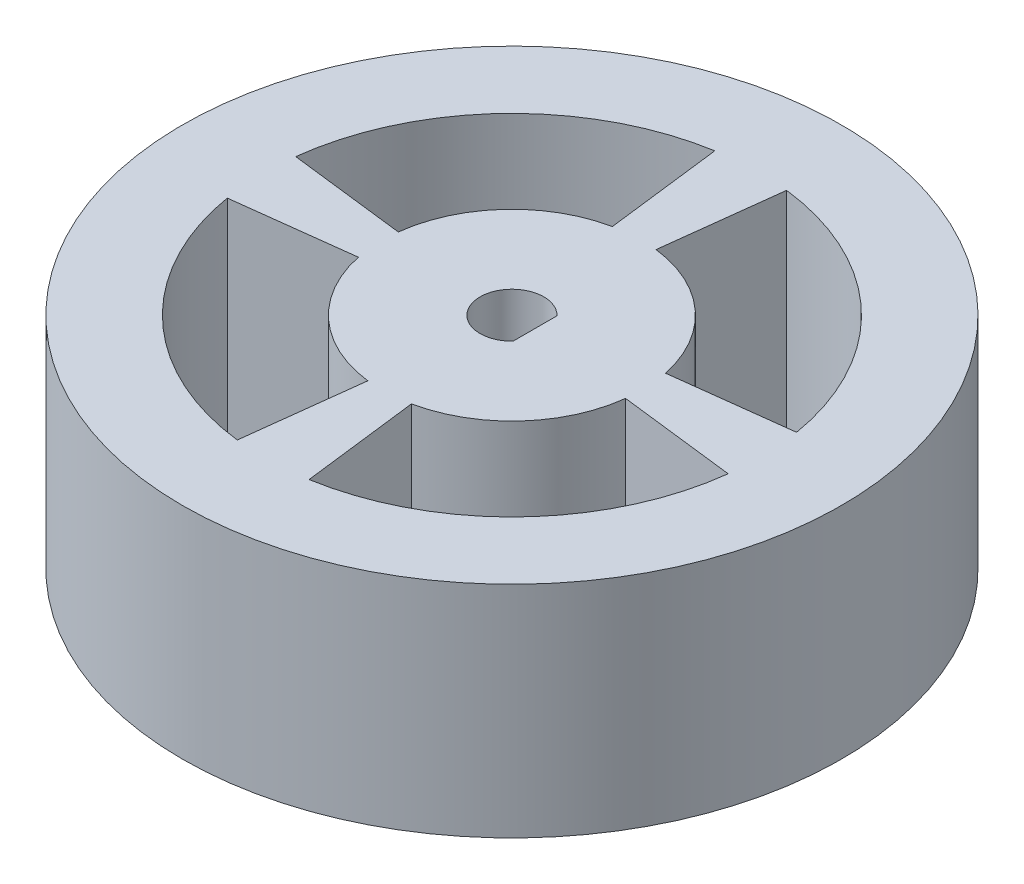
SolidWorks part; units mm, degrees
ref_plane "Plano frontal" through (0, 0, 0) normal (0, 0, 1) x (1, 0, 0)
ref_plane "Plano superior" through (0, 0, 0) normal (0, 1, 0) x (1, 0, 0)
ref_plane "Plano direito" through (0, 0, 0) normal (1, 0, 0) x (0, 0, -1)
sketch "Esboço1" plane through (0, 0, 0) normal (0, 1, 0) x (1, 0, 0)
  line L0 (-1.45, 0) -> (1.05, 0) construction
  line L1 (1.05, -1) -> (1.05, 1)
  line L2 (1.2085, -5.7812) -> (1.8617, -11.0949)
  line L3 (5.8652, -0.6936) -> (11.1711, -1.33)
  line L4 (-5.7812, -1.2085) -> (-11.0949, -1.8617)
  line L5 (-0.6936, -5.8652) -> (-1.33, -11.1711)
  line L6 (-1.2085, 5.7812) -> (-1.8617, 11.0949)
  line L7 (-5.8652, 0.6936) -> (-11.1711, 1.33)
  line L8 (5.7812, 1.2085) -> (11.0949, 1.8617)
  line L9 (0.6936, 5.8652) -> (1.33, 11.1711)
  circle A0 centre (0, 0) radius 15
  circle A1 centre (0, 0) radius 1.45 construction
  arc A3 (1.05, -1) -> (1.05, 1) centre (0, 0) cw
  circle A4 centre (0, 0) radius 5.9061 construction
  circle A5 centre (0, 0) radius 11.25 construction
  arc A6 (5.8652, -0.6936) -> (1.2085, -5.7812) centre (0, 0) cw
  arc A7 (11.1711, -1.33) -> (1.8617, -11.0949) centre (0, 0) cw
  arc A8 (-0.6936, -5.8652) -> (-5.7812, -1.2085) centre (0, 0) cw
  arc A9 (-1.33, -11.1711) -> (-11.0949, -1.8617) centre (0, 0) cw
  arc A10 (-5.8652, 0.6936) -> (-1.2085, 5.7812) centre (0, 0) cw
  arc A11 (-11.1711, 1.33) -> (-1.8617, 11.0949) centre (0, 0) cw
  arc A12 (0.6936, 5.8652) -> (5.7812, 1.2085) centre (0, 0) cw
  arc A13 (1.33, 11.1711) -> (11.0949, 1.8617) centre (0, 0) cw
  point P9 (1.05, 0)
  point P30 (0, 0)
  dimension "D1" = 30
  dimension "D2" = 2.9
  dimension "D5" = 22.5
  dimension "D3" = 2.5
  dimension "D4" = 4
extrude "Ressalto-extrusão1" add sketch "Esboço1" along normal blind 10
